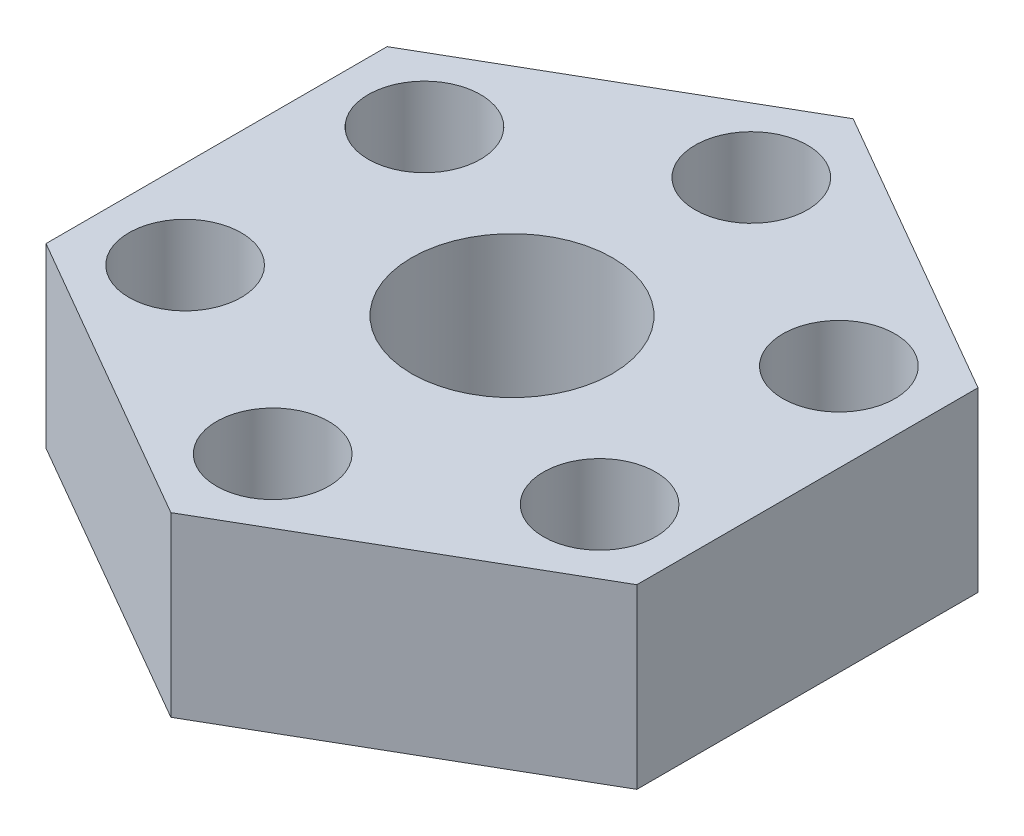
SolidWorks part; units mm, degrees
ref_plane "Front Plane" through (0, 0, 0) normal (0, 0, 1) x (1, 0, 0)
ref_plane "Top Plane" through (0, 0, 0) normal (0, 1, 0) x (1, 0, 0)
ref_plane "Right Plane" through (0, 0, 0) normal (1, 0, 0) x (0, 0, -1)
sketch "Sketch1" plane through (0, 0, 0) normal (0, 1, 0) x (1, 0, 0)
  line L0 (-5, -2.8868) -> (0, -5.7735) construction
  line L1 (0, -5.7735) -> (5, -2.8868) construction
  line L2 (5, -2.8868) -> (5, 2.8868) construction
  line L3 (5, 2.8868) -> (0, 5.7735) construction
  line L4 (0, 5.7735) -> (-5, 2.8868) construction
  line L5 (-5, 2.8868) -> (-5, -2.8868) construction
  line L6 (-5, -2.8868) -> (0, -5.7735)
  line L7 (0, -5.7735) -> (5, -2.8868)
  line L8 (5, -2.8868) -> (5, 2.8868)
  line L9 (5, 2.8868) -> (0, 5.7735)
  line L10 (0, 5.7735) -> (-5, 2.8868)
  line L11 (-5, 2.8868) -> (-5, -2.8868)
  line L12 (0, 0) -> (-5, 2.8868) construction
  circle A0 centre (0, 0) radius 1.7
  circle A1 centre (-3.5074, 2.025) radius 0.95
  circle A2 centre (0, 0) radius 5 construction
  circle A3 centre (0, 4.05) radius 0.95
  circle A4 centre (3.5074, 2.025) radius 0.95
  circle A5 centre (3.5074, -2.025) radius 0.95
  circle A6 centre (0, -4.05) radius 0.95
  circle A7 centre (-3.5074, -2.025) radius 0.95
  point P26 (0, 0)
  dimension "D1" = 3.4
  dimension "D2" = 1.9
  dimension "D3" = 6
extrude "Boss-Extrude1" add sketch "Sketch1" along normal blind 3
